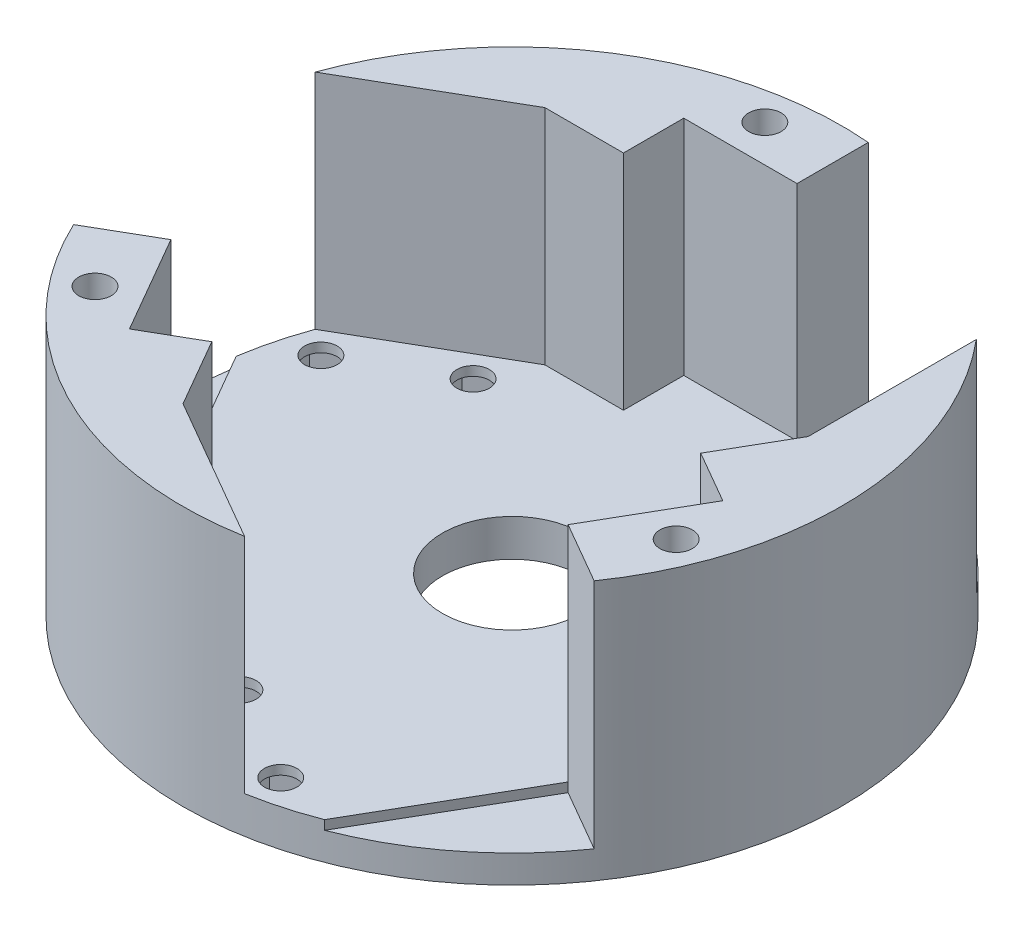
SolidWorks part; units mm, degrees
ref_plane "Front Plane" through (0, 0, 0) normal (0, 0, 1) x (1, 0, 0)
ref_plane "Top Plane" through (0, 0, 0) normal (0, 1, 0) x (1, 0, 0)
ref_plane "Right Plane" through (0, 0, 0) normal (1, 0, 0) x (0, 0, -1)
sketch "Sketch1" plane through (0, 0, 0) normal (0, 1, 0) x (1, 0, 0)
  circle A0 centre (0, 0) radius 35.5
  dimension "D1" = 71
extrude "Boss-Extrude1" add sketch "Sketch1" along normal mid plane 28
sketch "Sketch2" plane through (0, 14, 0) normal (0, 1, 0) x (1, 0, 0)
  line L0 (27.2, 27.7) -> (27.2, 4.7)
  line L1 (27.2, 4.7) -> (22.9648, -2.6355)
  line L2 (22.9648, -2.6355) -> (28.5889, -5.8826)
  line L3 (28.5889, -5.8826) -> (10.3889, -37.4059)
  line L4 (10.3889, -37.4059) -> (-9.5297, -25.9059)
  line L5 (-9.5297, -25.9059) -> (-13.7648, -18.5704)
  line L6 (-13.7648, -18.5704) -> (-19.3889, -21.8174)
  line L7 (-19.3889, -21.8174) -> (-37.5889, 9.7059)
  line L8 (-37.5889, 9.7059) -> (-17.6703, 21.2059)
  line L9 (-17.6703, 21.2059) -> (-9.2, 21.2059)
  line L10 (-9.2, 21.2059) -> (-9.2, 27.7)
  line L11 (-9.2, 27.7) -> (27.2, 27.7)
  line L12 (-25.3157, -11.1519) -> (-22.3954, -16.21) construction
  line L13 (-6.0644, -27.6756) -> (5.9112, -34.5897) construction
  line L14 (22.3157, -16.3481) -> (25.236, -11.29) construction
  line L15 (11.9356, 3.5013) -> (23.9112, -3.4128) construction
  line L16 (27, 8.5859) -> (27, 22.4141) construction
  line L17 (20.8405, 27.5) -> (15, 27.5) construction
  line L18 (-9, 8.5859) -> (-9, 22.4141) construction
  line L19 (-20.9356, 19.0897) -> (-32.9112, 12.1756) construction
  line L20 (-2.9356, -12.0872) -> (-14.9112, -19.0013) construction
  point P2 (28.0862, 27.7505)
  point P15 (27.6191, 22.5286)
  point P30 (-12.6213, -18.3481)
  point P33 (-9.706, -25.8041)
  dimension "D1" = 0.2
  dimension "D2" = 0.2
  dimension "D3" = 0.2
  dimension "D4" = 0.2
  dimension "D5" = 0.2
  dimension "D6" = 0.2
  dimension "D7" = 0.2
  dimension "D8" = 0.2
  dimension "D9" = 0.2
  dimension "D10" = 23
extrude "Cut-Extrude1" cut sketch "Sketch2" against normal blind 24
sketch "Sketch3" plane through (0, 14, 0) normal (0, 1, 0) x (1, 0, 0)
  line L0 (-35.4889, 6.0686) -> (-44.1492, 1.0686)
  line L1 (-35.0903, 5.3781) -> (-19.3889, -21.8174) construction
  line L2 (-44.1492, 1.0686) -> (-34.1492, -16.2519)
  line L3 (-34.1492, -16.2519) -> (-25.4889, -11.2519)
  line L4 (-25.4889, -11.2519) -> (-35.4889, 6.0686)
  line L5 (-25.3157, -11.1519) -> (-24.0167, -10.4019) construction
  line L6 (23, 27.7) -> (23, 37.7)
  line L7 (23, 37.7) -> (3, 37.7)
  line L8 (3, 37.7) -> (3, 27.7)
  line L9 (3, 27.7) -> (23, 27.7)
  line L10 (12.4889, -33.7686) -> (21.1492, -38.7686)
  line L11 (21.1492, -38.7686) -> (31.1492, -21.4481)
  line L12 (31.1492, -21.4481) -> (22.4889, -16.4481)
  line L13 (22.4889, -16.4481) -> (12.4889, -33.7686)
  dimension "D1" = 20
  dimension "D2" = 10
  dimension "D3" = 3
extrude "Cut-Extrude2" cut sketch "Sketch3" against normal blind 25
sketch "Sketch4" plane through (0, 14, 0) normal (0, 1, 0) x (1, 0, 0)
  line L0 (-4.4535, 31.6886) -> (0, 0) construction
  line L1 (0, 0) -> (0, 53.1754) construction
  circle A1 centre (-4.4535, 31.6886) radius 1.75
  circle A2 centre (29.6699, -11.9874) radius 1.75
  circle A3 centre (-25.2163, -19.7012) radius 1.75
  dimension "D1" = 3.5
  dimension "D2" = 32
  dimension "D4" = 8
  dimension "D3" = 3
extrude "Cut-Extrude3" cut sketch "Sketch4" against normal through all
sketch "Sketch5" plane through (0, -14, 0) normal (0, -1, 0) x (1, 0, 0)
  line L1 (-26.8618, 22.5512) -> (-28.5072, 19.7012)
  line L2 (-28.5072, 19.7012) -> (-26.8618, 16.8512)
  line L3 (-26.8618, 16.8512) -> (-23.5709, 16.8512)
  line L4 (-23.5709, 16.8512) -> (-21.9254, 19.7012)
  line L5 (-21.9254, 19.7012) -> (-23.5709, 22.5512)
  line L6 (-23.5709, 22.5512) -> (-26.8618, 22.5512)
  line L7 (32.9608, 11.9874) -> (31.3153, 14.8374)
  line L8 (31.3153, 14.8374) -> (28.0244, 14.8374)
  line L9 (28.0244, 14.8374) -> (26.379, 11.9874)
  line L10 (26.379, 11.9874) -> (28.0244, 9.1374)
  line L11 (28.0244, 9.1374) -> (31.3153, 9.1374)
  line L12 (31.3153, 9.1374) -> (32.9608, 11.9874)
  line L13 (-6.099, -34.5386) -> (-2.8081, -34.5386)
  line L14 (-2.8081, -34.5386) -> (-1.1626, -31.6886)
  line L15 (-1.1626, -31.6886) -> (-2.8081, -28.8386)
  line L16 (-2.8081, -28.8386) -> (-6.099, -28.8386)
  line L17 (-6.099, -28.8386) -> (-7.7444, -31.6886)
  line L18 (-7.7444, -31.6886) -> (-6.099, -34.5386)
  line L19 (-25.4889, 11.2519) -> (-19.3889, 21.8174) construction
  circle A0 centre (-25.2163, 19.7012) radius 2.85 construction
  circle A1 centre (29.6699, 11.9874) radius 2.85 construction
  circle A2 centre (-4.4535, -31.6886) radius 2.85 construction
  point P12 (-4.4535, -31.6886)
  dimension "D1" = 5.7
  dimension "D2" = 3
extrude "Cut-Extrude4" cut sketch "Sketch5" against normal blind 3
sketch "Sketch6" plane through (0, -14, 0) normal (0, -1, 0) x (1, 0, 0)
  circle A0 centre (6.6195, 31.5346) radius 1.75
  circle A1 centre (-3.7728, 25.5346) radius 1.75
  circle A2 centre (24, -21.5) radius 1.75
  circle A3 centre (24, -9.5) radius 1.75
  circle A4 centre (-30.6195, -10.0346) radius 1.75
  circle A5 centre (-20.2272, -16.0346) radius 1.75
  dimension "D1" = 3.5
  dimension "D2" = 3
extrude "Cut-Extrude5" cut sketch "Sketch6" against normal through all
sketch "Sketch7" plane through (0, -14, 0) normal (0, -1, 0) x (1, 0, 0)
  line L0 (9.4695, 29.8892) -> (9.4695, 33.1801)
  line L1 (-30.6195, -6.7437) -> (-33.4695, -8.3892)
  line L2 (-33.4695, -8.3892) -> (-33.4695, -11.6801)
  line L3 (-33.4695, -11.6801) -> (-30.6195, -13.3255)
  line L4 (-30.6195, -13.3255) -> (-27.7695, -11.6801)
  line L5 (-27.7695, -11.6801) -> (-27.7695, -8.3892)
  line L6 (-27.7695, -8.3892) -> (-30.6195, -6.7437)
  line L7 (-23.0772, -14.3892) -> (-23.0772, -17.6801)
  line L8 (-23.0772, -17.6801) -> (-20.2272, -19.3255)
  line L9 (-20.2272, -19.3255) -> (-17.3772, -17.6801)
  line L10 (-17.3772, -17.6801) -> (-17.3772, -14.3892)
  line L11 (-17.3772, -14.3892) -> (-20.2272, -12.7437)
  line L12 (-20.2272, -12.7437) -> (-23.0772, -14.3892)
  line L13 (9.4695, 33.1801) -> (6.6195, 34.8255)
  line L14 (6.6195, 34.8255) -> (3.7695, 33.1801)
  line L15 (3.7695, 33.1801) -> (3.7695, 29.8892)
  line L16 (3.7695, 29.8892) -> (6.6195, 28.2437)
  line L17 (6.6195, 28.2437) -> (9.4695, 29.8892)
  line L18 (-0.9228, 27.1801) -> (-3.7728, 28.8255)
  line L19 (-3.7728, 28.8255) -> (-6.6228, 27.1801)
  line L20 (-6.6228, 27.1801) -> (-6.6228, 23.8892)
  line L21 (-6.6228, 23.8892) -> (-3.7728, 22.2437)
  line L22 (-3.7728, 22.2437) -> (-0.9228, 23.8892)
  line L23 (-0.9228, 23.8892) -> (-0.9228, 27.1801)
  line L24 (21.15, -23.1454) -> (24, -24.7909)
  line L25 (24, -24.7909) -> (26.85, -23.1454)
  line L26 (26.85, -23.1454) -> (26.85, -19.8546)
  line L27 (26.85, -19.8546) -> (24, -18.2091)
  line L28 (24, -18.2091) -> (21.15, -19.8546)
  line L29 (21.15, -19.8546) -> (21.15, -23.1454)
  line L30 (24, -12.7909) -> (26.85, -11.1454)
  line L31 (26.85, -11.1454) -> (26.85, -7.8546)
  line L32 (26.85, -7.8546) -> (24, -6.2091)
  line L33 (24, -6.2091) -> (21.15, -7.8546)
  line L34 (21.15, -7.8546) -> (21.15, -11.1454)
  line L35 (21.15, -11.1454) -> (24, -12.7909)
  circle A0 centre (-30.6195, -10.0346) radius 2.85 construction
  circle A1 centre (-20.2272, -16.0346) radius 2.85 construction
  circle A2 centre (6.6195, 31.5346) radius 2.85 construction
  circle A3 centre (-3.7728, 25.5346) radius 2.85 construction
  circle A4 centre (24, -21.5) radius 2.85 construction
  circle A5 centre (24, -9.5) radius 2.85 construction
  dimension "D1" = 5.7
  dimension "D2" = 3
extrude "Cut-Extrude6" cut sketch "Sketch7" against normal blind 3
sketch "Sketch8" plane through (0, -10, 0) normal (0, 1, 0) x (1, 0, 0)
  circle A0 centre (0, 0) radius 7.5
  dimension "D1" = 15
extrude "Cut-Extrude7" cut sketch "Sketch8" against normal through all
